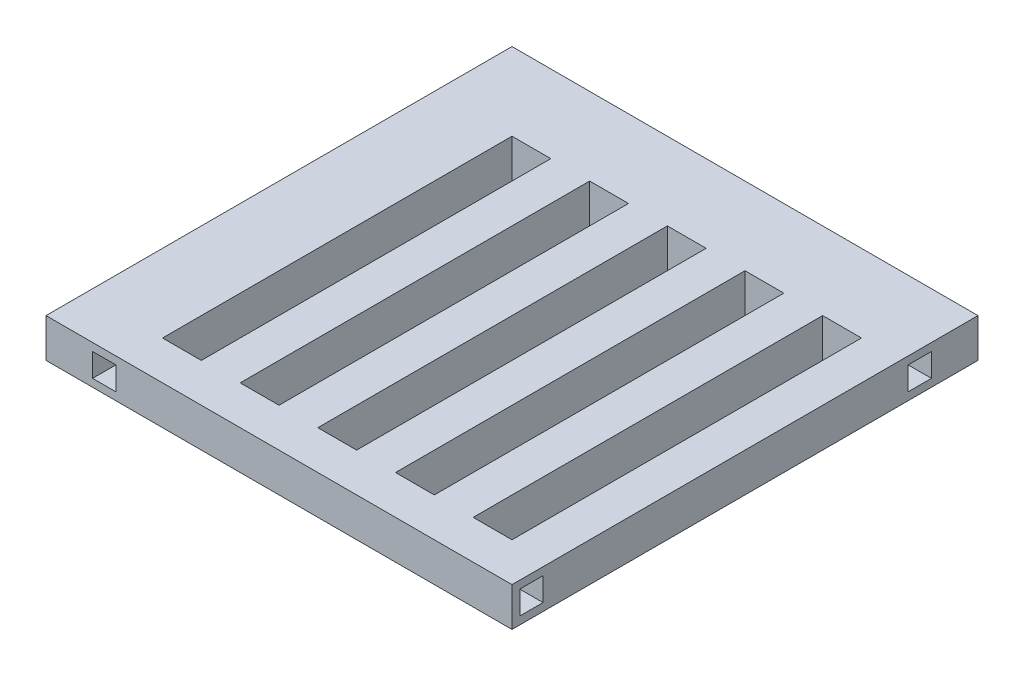
SolidWorks part; units mm, degrees
ref_plane "Front Plane" through (0, 0, 0) normal (0, 0, 1) x (1, 0, 0)
ref_plane "Top Plane" through (0, 0, 0) normal (0, 1, 0) x (1, 0, 0)
ref_plane "Right Plane" through (0, 0, 0) normal (1, 0, 0) x (0, 0, -1)
sketch "Sketch3" plane through (0, 0, 0) normal (0, 1, 0) x (1, 0, 0)
  line L1 (0, 0) -> (-152.4, 0)
  line L2 (0, 0) -> (0, 152.4)
  line L3 (0, 152.4) -> (-152.4, 152.4)
  line L4 (-152.4, 0) -> (-152.4, 152.4)
  dimension "D1" = 152.4
  dimension "D2" = 152.4
extrude "Boss-Extrude1" add sketch "Sketch3" along normal blind 12.7
sketch "Sketch5" plane through (-152.4, 0, 0) normal (-1, 0, 0) x (0, 0, 1)
  line L0 (-149.86, 2.54) -> (-149.86, 10.16)
  line L5 (-149.86, 10.16) -> (-2.54, 10.16)
  line L6 (-2.54, 2.54) -> (-2.54, 10.16)
  line L7 (-149.86, 2.54) -> (-2.54, 2.54)
extrude "Cut-Extrude1" cut sketch "Sketch5" against normal blind 12.7
sketch "Sketch6" plane through (0, 12.7, 0) normal (0, 1, 0) x (1, 0, 0)
  line L0 (-139.7, 12.7) -> (-139.7, 139.7)
  line L5 (-127, 12.7) -> (-127, 139.7)
  line L6 (-114.3, 12.7) -> (-114.3, 139.7)
  line L7 (-101.6, 12.7) -> (-101.6, 139.7)
  line L8 (-88.9, 12.7) -> (-88.9, 139.7)
  line L9 (-76.2, 12.7) -> (-76.2, 139.7)
  line L10 (-63.5, 12.7) -> (-63.5, 139.7)
  line L11 (-50.8, 12.7) -> (-50.8, 139.7)
  line L12 (-38.1, 12.7) -> (-38.1, 139.7)
  line L13 (-25.4, 12.7) -> (-25.4, 139.7)
  line L14 (-12.7, 12.7) -> (-12.7, 139.7)
  line L15 (-12.7, 12.7) -> (-12.7, 139.7)
  line L16 (-12.7, 139.7) -> (-139.7, 139.7)
  line L17 (-12.7, 12.7) -> (-139.7, 12.7)
  line L18 (-127, 0) -> (-127, 152.4) construction
  line L19 (-114.3, 0) -> (-114.3, 152.4) construction
  line L20 (-101.6, 0) -> (-101.6, 152.4) construction
  line L21 (-88.9, 0) -> (-88.9, 152.4) construction
  line L22 (-76.2, 0) -> (-76.2, 152.4) construction
  line L23 (-63.5, 0) -> (-63.5, 152.4) construction
  line L24 (-50.8, 0) -> (-50.8, 152.4) construction
  line L25 (-38.1, 0) -> (-38.1, 152.4) construction
  line L26 (-25.4, 0) -> (-25.4, 152.4) construction
  line L27 (-12.7, 0) -> (-12.7, 152.4) construction
  line L31 (-139.7, 0) -> (-139.7, 152.4) construction
  dimension "D1" = 12.7
  dimension "D2" = 12.7
  dimension "D3" = 12.7
  dimension "D4" = 12.7
  dimension "D5" = 12.7
  dimension "D6" = 12.7
  dimension "D7" = 12.7
  dimension "D8" = 12.7
  dimension "D9" = 12.7
  dimension "D10" = 12.7
extrude "Cut-Extrude3" cut sketch "Sketch6" against normal blind 12.7 contours L17 L6 L16 L5 | L17 L8 L16 L7 | L17 L10 L16 L9 | L17 L12 L16 L11 | L17 L14 L16 L13
sketch "Sketch7" plane through (0, 0, 0) normal (1, 0, 0) x (0, 0, -1)
  line L0 (0, 0) -> (152.4, 0) construction
  line L1 (0, 12.7) -> (12.7, 12.7)
  line L2 (0, 12.7) -> (0, 0)
  line L3 (0, 0) -> (12.7, 0)
  line L4 (12.7, 12.7) -> (12.7, 0)
  dimension "D1" = 12.7
sketch "Sketch8" plane through (0, 0, 0) normal (1, 0, 0) x (0, 0, -1)
  line L15 (149.86, 10.16) -> (142.24, 10.16)
  line L16 (142.24, 2.54) -> (142.24, 10.16)
  line L17 (149.86, 2.54) -> (142.24, 2.54)
  line L18 (149.86, 2.54) -> (149.86, 10.16)
  line L19 (2.54, 2.54) -> (10.16, 2.54)
  line L20 (2.54, 10.16) -> (2.54, 2.54)
  line L21 (10.16, 2.54) -> (10.16, 10.16)
  line L22 (10.16, 10.16) -> (2.54, 10.16)
  line L23 (2.54, 2.54) -> (10.16, 2.54)
  line L24 (2.54, 10.16) -> (2.54, 2.54)
  line L25 (10.16, 2.54) -> (10.16, 10.16)
  line L26 (10.16, 10.16) -> (2.54, 10.16)
  dimension "D2" = 2.54
extrude "Cut-Extrude4" cut sketch "Sketch8" against normal blind 25.4
sketch "Sketch9" plane through (0, 0, 0) normal (0, 0, 1) x (1, 0, 0)
  line L8 (-129.54, 10.16) -> (-129.54, 2.54)
  line L9 (-137.16, 2.54) -> (-129.54, 2.54)
  line L10 (-137.16, 10.16) -> (-137.16, 2.54)
  line L11 (-137.16, 10.16) -> (-129.54, 10.16)
extrude "Cut-Extrude5" cut sketch "Sketch9" against normal blind 25.4
sketch "Sketch10" plane through (0, 0, -152.4) normal (0, 0, -1) x (-1, 0, 0)
  line L11 (137.16, 2.54) -> (137.16, 10.16)
  line L12 (137.16, 10.16) -> (129.6511, 10.16)
  line L13 (129.6511, 2.54) -> (129.6511, 10.16)
  line L14 (137.16, 2.54) -> (129.6511, 2.54)
extrude "Cut-Extrude6" cut sketch "Sketch10" against normal blind 25.4
sketch "Sketch11" plane through (-25.4, 0, 0) normal (1, 0, 0) x (0, 0, -1)
  line L1 (142.24, 2.54) -> (149.86, 2.54)
  line L2 (142.24, 2.54) -> (142.24, 10.16)
  line L3 (142.24, 10.16) -> (149.86, 10.16)
  line L4 (149.86, 2.54) -> (149.86, 10.16)
extrude "Boss-Extrude2" add sketch "Sketch11" along normal blind 25.4
sketch "Sketch12" plane through (0, 0, -152.4) normal (0, 0, -1) x (-1, 0, 0)
  line L1 (0, 12.7) -> (152.4, 12.7) construction
  line L4 (127.1355, 12.7) -> (0, 12.7)
  line L5 (127.1355, 12.7) -> (127.1355, 0)
  line L6 (127.1355, 0) -> (0, 0)
  line L7 (0, 12.7) -> (0, 0)
extrude "Boss-Extrude3" add sketch "Sketch12" against normal blind 25.4
sketch "Sketch14" plane through (0, 0, -152.4) normal (0, 0, -1) x (-1, 0, 0)
  line L0 (2.54, 2.54) -> (2.54, 10.16)
  line L5 (2.54, 10.16) -> (124.46, 10.16)
  line L6 (124.46, 2.54) -> (124.46, 10.16)
  line L7 (2.54, 2.54) -> (124.46, 2.54)
extrude "Cut-Extrude7" cut sketch "Sketch14" against normal blind 12.7
sketch "Sketch15" plane through (0, 0, 0) normal (1, 0, 0) x (0, 0, -1)
  line L7 (137.16, 2.54) -> (129.54, 2.54)
  line L8 (137.16, 10.16) -> (129.54, 10.16)
  line L9 (129.54, 2.54) -> (129.54, 10.16)
  line L10 (137.16, 2.54) -> (137.16, 10.16)
extrude "Cut-Extrude9" cut sketch "Sketch15" against normal blind 25.4
